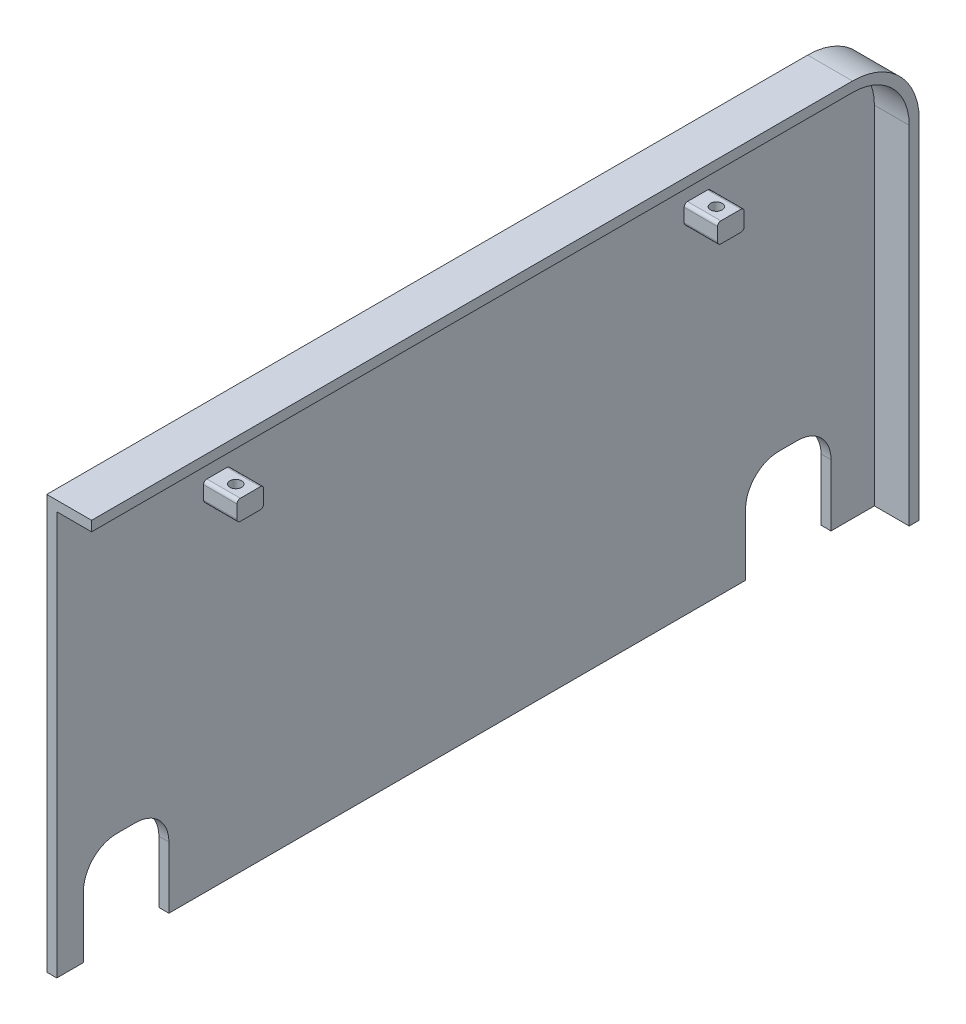
SolidWorks part; units mm, degrees
ref_plane "Front Plane" through (0, 0, 0) normal (0, 0, 1) x (1, 0, 0)
ref_plane "Top Plane" through (0, 0, 0) normal (0, 1, 0) x (1, 0, 0)
ref_plane "Right Plane" through (0, 0, 0) normal (1, 0, 0) x (0, 0, -1)
sketch "Sketch1" plane through (0, 0, 0) normal (1, 0, 0) x (0, 0, -1)
  line L0 (-77.887, -82.1549) -> (77.913, -82.1549)
  line L1 (-124.987, 51.8451) -> (125.013, 51.8451)
  line L2 (-124.987, 51.8451) -> (-124.987, -82.1549)
  line L3 (-124.987, -82.1549) -> (-94.887, -82.1549)
  line L4 (125.013, 51.8451) -> (125.013, -82.1549)
  line L15 (0.013, 51.8451) -> (0.013, -82.1549) construction
  line L16 (94.913, -82.1549) -> (125.013, -82.1549)
  line L17 (-94.887, -82.1549) -> (-77.887, -82.1549) construction
  line L18 (-94.887, -82.1549) -> (-94.887, -78.1549)
  line L20 (-77.887, -78.1549) -> (-77.887, -82.1549)
  line L21 (77.913, -78.1549) -> (77.913, -82.1549)
  line L22 (94.913, -82.1549) -> (94.913, -78.1549)
  circle A6 centre (-101.987, -28.6549) radius 10
  circle A7 centre (102.013, -28.6549) radius 10
  arc A10 (-77.887, -78.1549) -> (-94.887, -78.1549) centre (-86.387, -78.1549) ccw
  arc A11 (77.913, -78.1549) -> (94.913, -78.1549) centre (86.413, -78.1549) cw
  dimension "D3" = 4
  dimension "D7" = 23
  dimension "D8" = 20
  dimension "D9" = 53.5
  dimension "D4" = 17
  dimension "D1" = 250
  dimension "D2" = 134
extrude "Boss-Extrude1" add sketch "Sketch1" against normal blind 3
sketch "Sketch2" plane through (-3, 0, 0) normal (-1, 0, 0) x (0, 0, 1)
  line L0 (-125.013, 51.8451) -> (-72.013, 51.8451) construction
  line L1 (-125.013, 51.8451) -> (124.987, 51.8451) construction
  line L2 (-72.013, 51.8451) -> (-72.013, 59.8451) construction
  line L3 (-0.013, 51.8451) -> (-0.013, -82.1549) construction
  line L4 (-75.013, 59.8451) -> (-69.013, 59.8451)
  line L5 (-76.013, 58.8451) -> (-76.013, 54.8451)
  line L6 (-75.013, 53.8451) -> (-69.013, 53.8451)
  line L7 (-68.013, 58.8451) -> (-68.013, 54.8451)
  line L8 (77.887, -82.1549) -> (-77.913, -82.1549) construction
  line L9 (71.987, 51.8451) -> (71.987, 59.8451) construction
  line L10 (124.987, 51.8451) -> (71.987, 51.8451) construction
  line L11 (67.987, 58.8451) -> (67.987, 54.8451)
  line L12 (74.987, 53.8451) -> (68.987, 53.8451)
  line L13 (75.987, 58.8451) -> (75.987, 54.8451)
  line L14 (74.987, 59.8451) -> (68.987, 59.8451)
  arc A0 (-69.013, 59.8451) -> (-68.013, 58.8451) centre (-69.013, 58.8451) cw
  arc A1 (-69.013, 53.8451) -> (-68.013, 54.8451) centre (-69.013, 54.8451) ccw
  arc A2 (-76.013, 54.8451) -> (-75.013, 53.8451) centre (-75.013, 54.8451) ccw
  arc A3 (-75.013, 59.8451) -> (-76.013, 58.8451) centre (-75.013, 58.8451) ccw
  arc A4 (74.987, 59.8451) -> (75.987, 58.8451) centre (74.987, 58.8451) cw
  arc A5 (75.987, 54.8451) -> (74.987, 53.8451) centre (74.987, 54.8451) cw
  arc A6 (68.987, 53.8451) -> (67.987, 54.8451) centre (68.987, 54.8451) cw
  arc A7 (68.987, 59.8451) -> (67.987, 58.8451) centre (68.987, 58.8451) ccw
  point P10 (-72.013, 59.8451)
  point P17 (-76.013, 53.8451)
  point P20 (-76.013, 59.8451)
  point P40 (75.987, 59.8451)
  point P41 (75.987, 53.8451)
  dimension "D5" = 1
  dimension "D1" = 53
  dimension "D2" = 2
  dimension "D3" = 8
extrude "Boss-Extrude2" add sketch "Sketch2" along normal blind 10
sketch "Sketch3" plane through (0, 59.8451, 0) normal (0, 1, 0) x (1, 0, 0)
  line L3 (-3, 0.013) -> (-19.4349, 0.013) construction
  line L4 (-3, 125.013) -> (-3, -124.987) construction
  line L5 (-13, -71.987) -> (-3, -71.987) construction
  circle A0 centre (-8.6365, 72.013) radius 1.7353
  circle A1 centre (-8.6365, -71.987) radius 1.7353
sketch "Sketch4" plane through (0, 53.8451, 0) normal (0, -1, 0) x (1, 0, 0)
  line L0 (-13, -72.013) -> (-3, -72.013) construction
  line L14 (-13, -75.013) -> (-13, -69.013) construction
  line L15 (-3, -75.013) -> (-3, -69.013) construction
  line L16 (-3, 71.987) -> (-13, 71.987) construction
  line L17 (-3, 68.987) -> (-3, 74.987) construction
  line L18 (-13, 68.987) -> (-13, 74.987) construction
  line L19 (-8.6365, 71.987) -> (-8.6365, -72.013) construction
  circle A1 centre (-8.6365, 71.987) radius 3
  circle A3 centre (-8.6365, -72.013) radius 3
  dimension "D1" = 6
  dimension "D2" = 6
sketch "Sketch5" plane through (0, 0, 0) normal (1, 0, 0) x (0, 0, -1)
  line L1 (-124.987, 51.8451) -> (125.013, 51.8451)
  line L2 (-124.987, 51.8451) -> (-124.987, 76.8451)
  line L10 (0.013, 76.8451) -> (0.013, -82.1549) construction
  line L11 (-77.887, -82.1549) -> (77.913, -82.1549) construction
  line L12 (0.013, -2.6549) -> (173.6231, -2.6549) construction
  line L21 (125.013, 51.8451) -> (125.013, -82.1549)
  line L23 (-124.987, 76.8451) -> (108.013, 76.8451)
  line L24 (128.013, 56.8451) -> (128.013, -82.1549)
  line L25 (128.013, -82.1549) -> (125.013, -82.1549)
  arc A8 (108.013, 76.8451) -> (128.013, 56.8451) centre (108.013, 56.8451) cw
  dimension "D2" = 3
  dimension "D1" = 20
extrude "Boss-Extrude3" add sketch "Sketch5" against normal up to surface (3 mm away) up to face at (-3, -28.6549, -92.013)
sketch "Sketch6" plane through (0, 76.8451, 0) normal (0, 1, 0) x (1, 0, 0)
  line L2 (-83.2765, 76.013) -> (-73.2765, 76.013) construction
  line L3 (-83.2765, 76.013) -> (-83.2765, 68.9594) construction
  line L4 (-83.2765, 68.9594) -> (-73.2765, 68.9594) construction
  line L5 (-73.2765, 76.013) -> (-73.2765, 68.9594) construction
  line L6 (-13, 76.013) -> (-3, 76.013) construction
  line L7 (-13, 76.013) -> (-13, 68.013) construction
  line L10 (-83.2765, -124.987) -> (-86.2765, -124.987)
  line L14 (-8.6365, 0.013) -> (-65.4749, 0.013) construction
  line L15 (-73.2765, -75.987) -> (-73.2765, -68.9334) construction
  line L16 (-83.2765, -68.9334) -> (-73.2765, -68.9334) construction
  line L17 (-83.2765, -75.987) -> (-83.2765, -68.9334) construction
  line L18 (-83.2765, -75.987) -> (-73.2765, -75.987) construction
  line L19 (-83.2765, 128.013) -> (-86.2765, 128.013)
  line L23 (-83.2765, 128.013) -> (-83.2765, -124.987)
  line L24 (-86.2765, -124.987) -> (-86.2765, 128.013)
  line L26 (-86.2765, 135.013) -> (-113.3718, 135.013) construction
  circle A1 centre (-77.6365, 72.013) radius 1.735 construction
  circle A6 centre (-77.6365, -71.987) radius 1.735 construction
  dimension "D2" = 3.47
  dimension "D3" = 4
  dimension "D4" = 5.64
  dimension "D5" = 10
extrude "Boss-Extrude4" add sketch "Sketch6" against normal up to surface (159 mm away) separate body up to face at (-1.5, -82.1549, -111.463)
sketch "Sketch8" plane through (-83.2765, 0, 0) normal (-1, 0, 0) x (0, 0, 1)
  line L0 (-75.013, 59.8451) -> (-69.013, 59.8451)
  line L1 (-68.013, 58.8451) -> (-68.013, 54.8451)
  line L2 (-69.013, 53.8451) -> (-75.013, 53.8451)
  line L3 (-76.013, 54.8451) -> (-76.013, 58.8451)
  line L4 (68.987, 59.8451) -> (74.987, 59.8451)
  line L5 (75.987, 58.8451) -> (75.987, 54.8451)
  line L6 (74.987, 53.8451) -> (68.987, 53.8451)
  line L7 (67.987, 54.8451) -> (67.987, 58.8451)
  arc A0 (-69.013, 59.8451) -> (-68.013, 58.8451) centre (-69.013, 58.8451) cw
  arc A1 (-68.013, 54.8451) -> (-69.013, 53.8451) centre (-69.013, 54.8451) cw
  arc A2 (-75.013, 53.8451) -> (-76.013, 54.8451) centre (-75.013, 54.8451) cw
  arc A3 (-76.013, 58.8451) -> (-75.013, 59.8451) centre (-75.013, 58.8451) cw
  arc A4 (74.987, 59.8451) -> (75.987, 58.8451) centre (74.987, 58.8451) cw
  arc A5 (75.987, 54.8451) -> (74.987, 53.8451) centre (74.987, 54.8451) cw
  arc A6 (68.987, 53.8451) -> (67.987, 54.8451) centre (68.987, 54.8451) cw
  arc A7 (67.987, 58.8451) -> (68.987, 59.8451) centre (68.987, 58.8451) cw
extrude "Boss-Extrude6" add sketch "Sketch8" against normal blind 10
sketch "Sketch9" plane through (0, 59.8451, 0) normal (0, 1, 0) x (1, 0, 0)
  line L0 (-83.2765, 72.013) -> (-3, 72.013) construction
  line L1 (-83.2765, 69.013) -> (-83.2765, 75.013) construction
  line L2 (-3, 69.013) -> (-3, 75.013) construction
  line L3 (-43.1383, 72.013) -> (-43.1383, -18.9939) construction
  circle A0 centre (-77.6365, -71.987) radius 1.735
  circle A1 centre (-77.6365, 72.013) radius 1.735
  circle A2 centre (-8.64, -71.987) radius 1.735
  circle A3 centre (-8.64, 72.013) radius 1.735
  dimension "D1" = 3.47
extrude "Cut-Extrude3" cut sketch "Sketch9" against normal blind 10
sketch "Sketch11" plane through (-3, 0, 0) normal (-1, 0, 0) x (0, 0, 1)
  line L5 (124.987, 73.8451) -> (124.987, 76.8451)
  line L6 (-125.013, -82.1549) -> (-128.013, -82.1549)
  line L7 (-125.013, 56.8451) -> (-125.013, -82.1549)
  line L8 (124.987, 73.8451) -> (-108.013, 73.8451)
  line L9 (-125.013, 56.8451) -> (-125.013, -82.1549)
  line L10 (124.987, 73.8451) -> (-108.013, 73.8451)
  line L11 (-128.013, -82.1549) -> (-128.013, 56.8451)
  line L12 (-108.013, 76.8451) -> (124.987, 76.8451)
  arc A2 (-128.013, 56.8451) -> (-108.013, 76.8451) centre (-108.013, 56.8451) cw
  arc A3 (-108.013, 73.8451) -> (-125.013, 56.8451) centre (-108.013, 56.8451) ccw
  arc A4 (-108.013, 73.8451) -> (-125.013, 56.8451) centre (-108.013, 56.8451) ccw
  dimension "D1" = 3
extrude "Boss-Extrude7" add sketch "Sketch11" along normal up to surface (80.2765 mm away) up to face at (-83.2765, 56.8451, 71.987)
sketch "Sketch13" plane through (0, 0, 0) normal (1, 0, 0) x (0, 0, -1)
  line L0 (-111.987, -28.6549) -> (-111.987, -82.1549)
  line L1 (-124.987, -82.1549) -> (-94.887, -82.1549) construction
  line L7 (94.913, -82.1549) -> (128.013, -82.1549) construction
  line L8 (112.013, -82.1549) -> (112.013, -28.6549)
  line L10 (-77.887, -78.1549) -> (-77.887, -82.1549) construction
  line L16 (-101.987, -18.6549) -> (-96.387, -18.6549)
  line L17 (-86.387, -28.6549) -> (-86.387, -69.6549)
  line L18 (102.013, -18.6549) -> (96.413, -18.6549)
  line L19 (86.413, -28.6549) -> (86.413, -69.6549)
  line L21 (-77.887, -78.1549) -> (-77.887, -82.1549)
  line L22 (-77.887, -82.1549) -> (-111.987, -82.1549)
  line L24 (77.913, -78.1549) -> (77.913, -82.1549)
  line L25 (-124.987, -82.1549) -> (125.013, -82.1549) construction
  line L26 (77.913, -82.1549) -> (112.013, -82.1549)
  arc A0 (-101.987, -18.6549) -> (-111.987, -28.6549) centre (-101.987, -28.6549) ccw
  arc A1 (112.013, -28.6549) -> (102.013, -18.6549) centre (102.013, -28.6549) ccw
  arc A2 (-86.387, -69.6549) -> (-77.887, -78.1549) centre (-86.387, -78.1549) cw
  arc A3 (77.913, -78.1549) -> (86.413, -69.6549) centre (86.413, -78.1549) cw
  arc A4 (-96.387, -18.6549) -> (-86.387, -28.6549) centre (-96.387, -28.6549) cw
  arc A5 (96.413, -18.6549) -> (86.413, -28.6549) centre (96.413, -28.6549) ccw
  dimension "D1" = 10
  dimension "D2" = 10
extrude "Cut-Extrude6" cut sketch "Sketch13" against normal blind 143
sketch "Sketch14" plane through (0, 0, 0) normal (1, 0, 0) x (0, 0, -1)
  line L1 (-124.987, -82.1549) -> (128.013, -82.1549)
  line L2 (-124.987, -82.1549) -> (-124.987, -47.1549)
  line L7 (-124.987, -47.1549) -> (128.013, -47.1549)
  line L8 (128.013, -82.1549) -> (128.013, -47.1549)
  line L9 (128.013, 56.8451) -> (128.013, -82.1549) construction
  dimension "D1" = 35
extrude "Cut-Extrude7" cut sketch "Sketch14" against normal blind 143
sketch "Sketch15" plane through (0, 0, 0) normal (1, 0, 0) x (0, 0, -1)
  line L8 (108.013, 76.8451) -> (128.013, 76.8451)
  line L9 (128.013, 76.8451) -> (128.013, 56.8451)
  line L14 (128.013, 56.8451) -> (128.013, -47.1549) construction
  line L15 (128.013, 56.8451) -> (128.013, 76.8451) construction
  arc A1 (128.013, 56.8451) -> (108.013, 76.8451) centre (108.013, 56.8451) ccw
extrude "Cut-Extrude8" cut sketch "Sketch15" against normal blind 143
sketch "Sketch17" plane through (0, 76.8451, 0) normal (0, 1, 0) x (1, 0, 0)
  circle A3 centre (-43.1388, -96.337) radius 2.5
  dimension "D6" = 5
extrude "Cut-Extrude9" cut sketch "Sketch17" against normal blind 143
sketch "Sketch18" plane through (0, 0, 0) normal (1, 0, 0) x (0, 0, -1)
  line L1 (-132.5686, 81.0343) -> (-119.987, 81.0343)
  line L2 (-132.5686, 81.0343) -> (-132.5686, -50.9934)
  line L3 (-132.5686, -50.9934) -> (-119.987, -50.9934)
  line L4 (-119.987, 81.0343) -> (-119.987, -50.9934)
extrude "Cut-Extrude10" cut sketch "Sketch18" against normal blind 143
sketch "Sketch29" plane through (0, 0, 0) normal (0, 0, 1) x (1, 0, 0)
  line L1 (-72.836, 80.8137) -> (15.2776, 80.8137)
  line L2 (-72.836, 80.8137) -> (-72.836, -54.4232)
  line L3 (-72.836, -54.4232) -> (15.2776, -54.4232)
  line L4 (15.2776, 80.8137) -> (15.2776, -54.4232)
extrude "Cut-Extrude19" cut sketch "Sketch29" against normal mid plane 300
